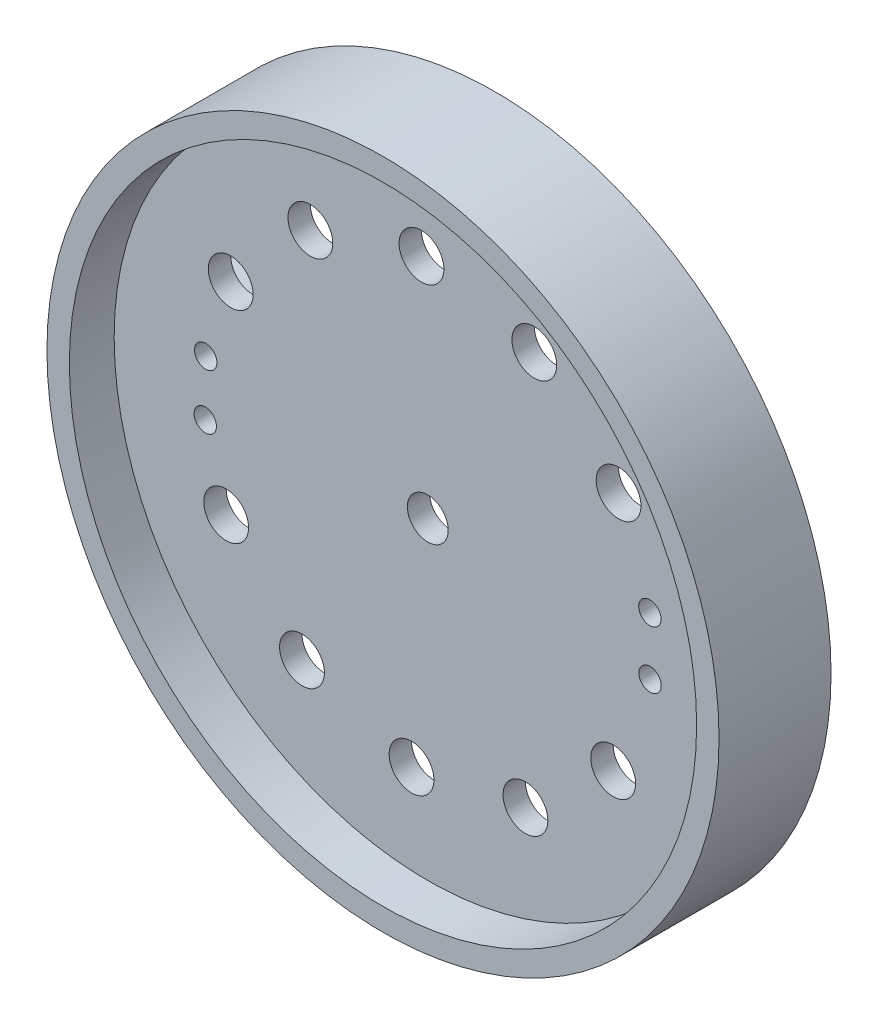
SolidWorks part; units mm, degrees
ref_plane "Front Plane" through (0, 0, 0) normal (0, 0, 1) x (1, 0, 0)
ref_plane "Top Plane" through (0, 0, 0) normal (0, 1, 0) x (1, 0, 0)
ref_plane "Right Plane" through (0, 0, 0) normal (1, 0, 0) x (0, 0, -1)
sketch "Sketch1" plane through (0, 0, 0) normal (0, 0, 1) x (1, 0, 0)
  circle A0 centre (0, 0) radius 38.1
  dimension "D1" = 76.2
extrude "Boss-Extrude2" add sketch "Sketch1" against normal blind 12.7 contours A0
sketch "Sketch3" plane through (0, 0, 0) normal (0, 0, 1) x (1, 0, 0)
  circle A0 centre (0, 0) radius 35.56
  dimension "D1" = 71.12
extrude "Cut-Extrude2" cut sketch "Sketch3" against normal blind 5.08
sketch "Sketch4" plane through (0, 0, -12.7) normal (0, 0, -1) x (-1, 0, 0)
  circle A0 centre (0, 0) radius 35.56
  dimension "D1" = 71.12
extrude "Cut-Extrude3" cut sketch "Sketch4" against normal blind 5.08
sketch "Sketch6" plane through (0, 0, -7.62) normal (0, 0, -1) x (-1, 0, 0)
  line L0 (-3.81, 0) -> (-35.56, 0)
  line L1 (-34.3483, -9.2036) -> (-3.6802, -0.9861)
  circle A0 centre (0, 0) radius 35.56 construction
  arc A1 (-35.56, 0) -> (-34.3483, -9.2036) centre (0, 0) ccw
  arc A2 (-3.81, 0) -> (-3.6802, -0.9861) centre (0, 0) ccw
  dimension "D1" = 7.62
  dimension "D2" = 15
extrude "Boss-Extrude3" add sketch "Sketch6" along normal up to surface (5.08 mm away) up to face at (-35.56, 0, -12.7)
mirror "Mirror2" about plane through (3.81, 0, -45.8818) normal (0, -1, 0) of "Boss-Extrude3"
sketch "Sketch8" plane through (0, 0, -7.62) normal (0, 0, -1) x (-1, 0, 0)
  line L0 (3.81, 0) -> (35.56, 0)
  line L1 (3.6802, -0.9861) -> (34.3483, -9.2036)
  arc A0 (-34.3483, -9.2036) -> (-34.3483, 9.2036) centre (0, 0) ccw construction
  arc A1 (34.3483, -9.2036) -> (35.56, 0) centre (0, 0) ccw
  arc A2 (3.6802, -0.9861) -> (3.81, 0) centre (0, 0) ccw
  dimension "D1" = 7.62
  dimension "D2" = 15
extrude "Boss-Extrude4" add sketch "Sketch8" along normal up to surface (5.08 mm away) up to face at (1.5696, 0, -12.7)
mirror "Mirror3" about plane through (-3.81, 0, -45.8818) normal (0, -1, 0) of "Boss-Extrude4"
sketch "Sketch9" plane through (0, 0, -7.62) normal (0, 0, -1) x (-1, 0, 0)
  circle A0 centre (0, 0) radius 25.4 construction
  circle A1 centre (22.3465, 12.0744) radius 2.54
  point P5 (22.3465, 12.0744)
  dimension "D1" = 50.8
  dimension "D2" = 5.08
extrude "Cut-Extrude5" cut sketch "Sketch9" against normal through all both and the other way through all contours A1
pattern_circular "CirPattern1" count 5 every 30 about axis through (0, 0, 0) along (0, 0, 1) of "Cut-Extrude5"
sketch "Sketch10" plane through (0, 0, -7.62) normal (0, 0, -1) x (-1, 0, 0)
  circle A0 centre (0, 0) radius 25.4 construction
  circle A1 centre (22.8606, -11.0704) radius 2.54
  dimension "D1" = 5.08
extrude "Cut-Extrude6" cut sketch "Sketch10" against normal through all both and the other way through all
pattern_circular "CirPattern2" count 5 every 30 about axis through (0, 0, 0) along (0, 0, 1) of "Cut-Extrude6"
sketch "Sketch11" plane through (0, 0, -7.62) normal (0, 0, -1) x (-1, 0, 0)
  circle A0 centre (0, 0) radius 25.4 construction
  circle A1 centre (-25.1805, 3.3318) radius 1.27
  circle A2 centre (-25.1987, -3.1916) radius 1.27
  circle A3 centre (25.1805, 3.3318) radius 1.27
  circle A4 centre (25.2295, -2.9379) radius 1.27
  dimension "D1" = 2.54
  dimension "D2" = 2.54
  dimension "D3" = 2.54
  dimension "D4" = 2.54
extrude "Cut-Extrude7" cut sketch "Sketch11" against normal through all both and the other way through all
sketch "Sketch12" plane through (0, 0, -7.62) normal (0, 0, -1) x (-1, 0, 0)
  circle A0 centre (0, 0) radius 2.3167
  dimension "D1" = 4.6335
extrude "Cut-Extrude8" cut sketch "Sketch12" against normal through all both and the other way through all
